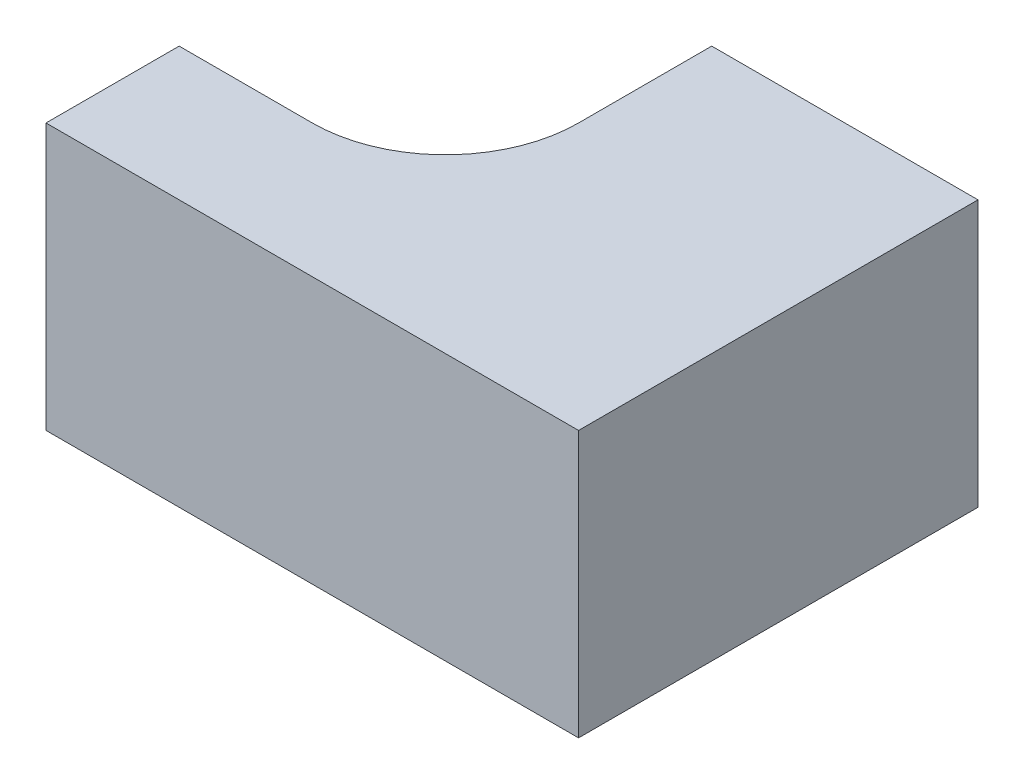
SolidWorks part; units mm, degrees
ref_plane "Přední rovina" through (0, 0, 0) normal (0, 0, 1) x (1, 0, 0)
ref_plane "Horní rovina" through (0, 0, 0) normal (0, 1, 0) x (1, 0, 0)
ref_plane "Pravá rovina" through (0, 0, 0) normal (1, 0, 0) x (0, 0, -1)
sketch "Sketch2" plane through (0, 0, 0) normal (0, 1, 0) x (1, 0, 0)
  line L0 (0, 0) -> (0, -10)
  line L1 (10, -20) -> (20, -20)
  line L2 (20, -20) -> (20, -30)
  line L3 (20, -30) -> (-20, -30)
  line L4 (-20, -30) -> (-20, 0)
  line L5 (-20, 0) -> (0, 0)
  arc A0 (0, -10) -> (10, -20) centre (10, -10) ccw
  dimension "D2" = 10
  dimension "D1" = 20
  dimension "D3" = 10
  dimension "D4" = 10
  dimension "D5" = 10
extrude "Boss-Extrude1" add sketch "Sketch2" along normal blind 20
mirror "Mirror1" about plane through (-20, 20, 30) normal (1, 0, 0) of bodies 101
delete or keep bodies "Body-Delete/Keep 1" type delete bodies bodies 101
equation "\"R\"= 10"
equation "\"D2@Sketch2\"=\"R\""
equation "\"D1@Sketch2\"=\"R\" *2"
equation "\"D3@Sketch2\"=\"R\" * 1"
equation "\"D5@Sketch2\"=\"R\""
equation "\"D4@Sketch2\"=\"R\""
